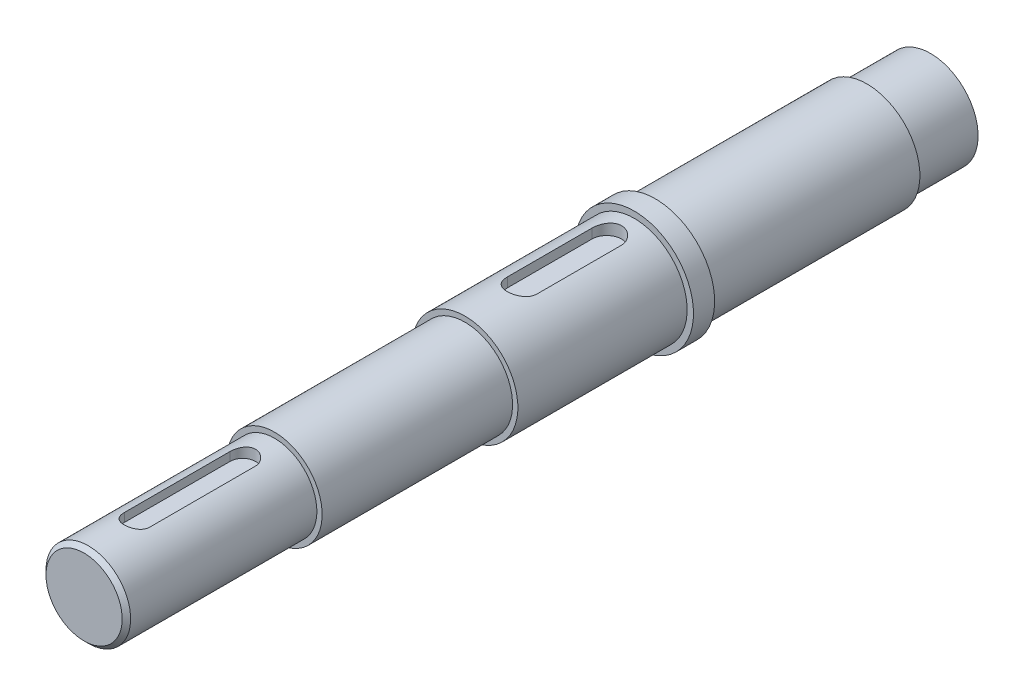
SolidWorks part; units mm, degrees
ref_plane "Front Plane" through (0, 0, 0) normal (0, 0, 1) x (1, 0, 0)
ref_plane "Top Plane" through (0, 0, 0) normal (0, 1, 0) x (1, 0, 0)
ref_plane "Right Plane" through (0, 0, 0) normal (1, 0, 0) x (0, 0, -1)
sketch "Sketch1" plane through (0, 0, 0) normal (0, 1, 0) x (1, 0, 0)
  line L0 (0, 0) -> (0, -400)
  line L3 (22.5, -30) -> (25, -30)
  line L4 (25, -30) -> (25, -130)
  line L5 (25, -130) -> (28, -130)
  line L7 (25, -220) -> (22.5, -220)
  line L8 (22.5, -220) -> (22.5, -310)
  line L9 (22.5, -310) -> (20, -310)
  line L10 (20, -310) -> (20, -400)
  line L11 (20, -400) -> (0, -400)
  line L12 (22.5, -30) -> (22.5, 0)
  line L13 (22.5, 0) -> (0, 0)
  line L14 (28, -130) -> (28, -140)
  line L15 (28, -140) -> (25, -140)
  line L16 (25, -140) -> (25, -220)
  dimension "D2" = 400
  dimension "D4" = 80
  dimension "D5" = 30
  dimension "D6" = 100
  dimension "D7" = 20
  dimension "D8" = 25
  dimension "D9" = 3
  dimension "D10" = 22.5
  dimension "D11" = 10
  dimension "D12" = 90
revolve "Revolve1" add sketch "Sketch1" angle 360 about L0
sketch "Sketch2" plane through (-0.9582, 7.9831, 400) normal (0, 0, 1) x (1, 0, 0)
  line L0 (0.9582, 12.0169) -> (0.9582, -7.9831) construction
  line L1 (0.9582, -7.9831) -> (0.9582, 12.0169) construction
  circle A0 centre (0.9582, -7.9831) radius 20 construction
  circle A2 centre (0.9582, -7.9831) radius 20
  dimension "Angle from vertical" = 360
ref_plane "Plane1" through (0, 20, 400) normal (0, -1, 0) x (-1, 0, 0)
sketch "Sketch3" plane through (0, 20, 400) normal (0, -1, 0) x (0, 0, 1)
  line L0 (-25, 0) -> (-75, 0) construction
  line L1 (-25, 6) -> (-75, 6)
  line L2 (-25, -6) -> (-75, -6)
  arc A0 (-25, 6) -> (-25, -6) centre (-25, 0) cw
  arc A1 (-75, 6) -> (-75, -6) centre (-75, 0) ccw
  dimension "Keyway width" = 12
  dimension "Distance from end face" = 25
  dimension "Length of slot" = 50
extrude "Cut-Extrude1" cut sketch "Sketch3" along normal blind 5
other "keyway (bs 4235 - part i)<1>"
sketch "Sketch22" plane through (8.0669, 22.5362, 220) normal (0, 0, 1) x (1, 0, 0)
  line L0 (-8.0669, 2.4638) -> (-8.0669, -22.5362) construction
  line L1 (-8.0669, -22.5362) -> (-8.0669, 2.4638) construction
  circle A0 centre (-8.0669, -22.5362) radius 25 construction
  circle A2 centre (-8.0669, -22.5362) radius 25
  dimension "Angle from vertical" = 0
ref_plane "Plane12" through (0, 25, 220) normal (0, -1, 0) x (-1, 0, 0)
sketch "Sketch32" plane through (0, 25, 220) normal (0, -1, 0) x (0, 0, 1)
  line L0 (-27, 0) -> (-67, 0) construction
  line L1 (-27, 7) -> (-67, 7)
  line L2 (-27, -7) -> (-67, -7)
  arc A0 (-27, 7) -> (-27, -7) centre (-27, 0) cw
  arc A1 (-67, 7) -> (-67, -7) centre (-67, 0) ccw
  dimension "Keyway width" = 14
  dimension "Distance from end face" = 27
  dimension "Length of slot" = 40
extrude "Cut-Extrude12" cut sketch "Sketch32" along normal blind 5.5
other "keyway (bs 4235 - part i)<2>"
chamfer "Chamfer1" distance 2 angle 45 1 edges at (-20, 0, 400)
